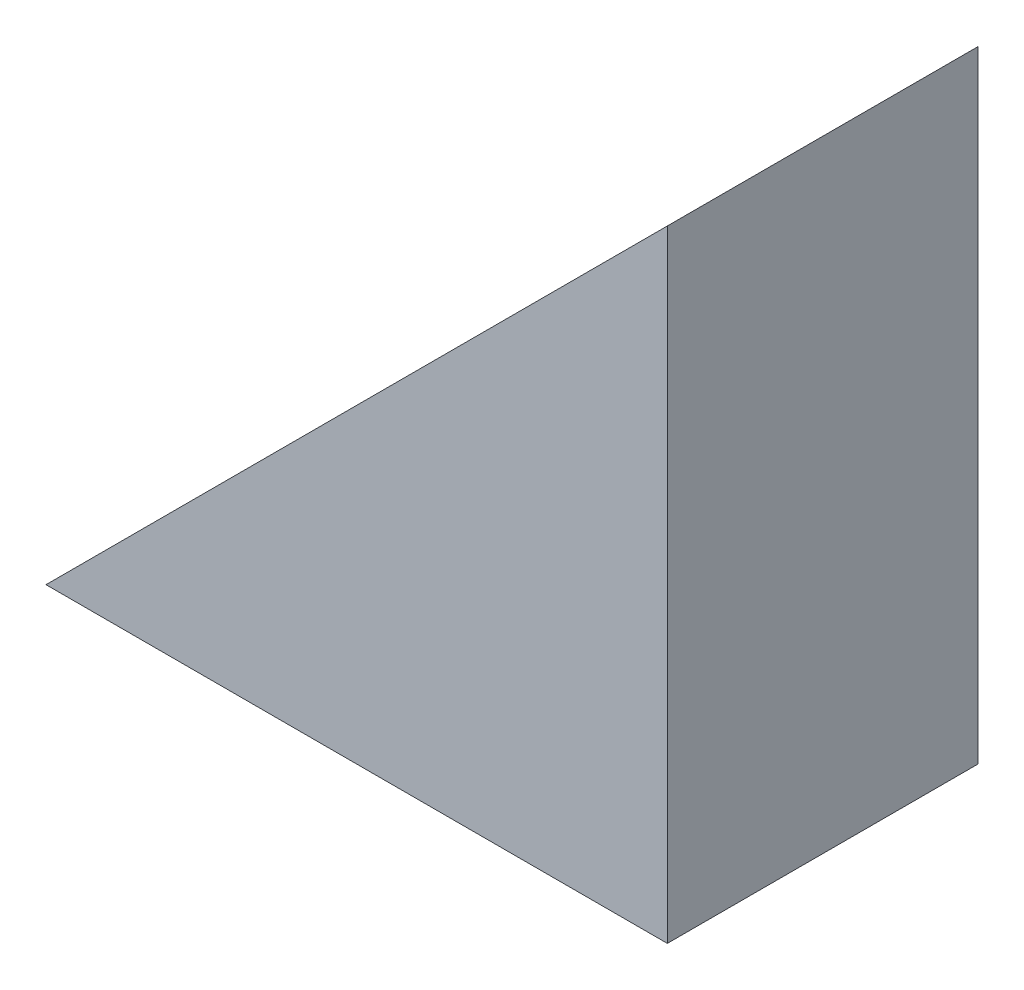
SolidWorks part; units mm, degrees
material "3.3315 (EN-AW 5005)"
ref_plane "Ebene vorne" through (0, 0, 0) normal (0, 0, 1) x (1, 0, 0)
ref_plane "Ebene oben" through (0, 0, 0) normal (0, 1, 0) x (1, 0, 0)
ref_plane "Ebene rechts" through (0, 0, 0) normal (1, 0, 0) x (0, 0, -1)
sketch "Skizze2" plane through (0, 0, 0) normal (0, 0, 1) x (1, 0, 0)
  line L0 (0, 0) -> (40, 0)
  line L1 (40, 0) -> (40, 40)
  line L2 (40, 40) -> (0, 0)
extrude "Aufsatz-Linear austragen1" add sketch "Skizze2" along normal blind 20
